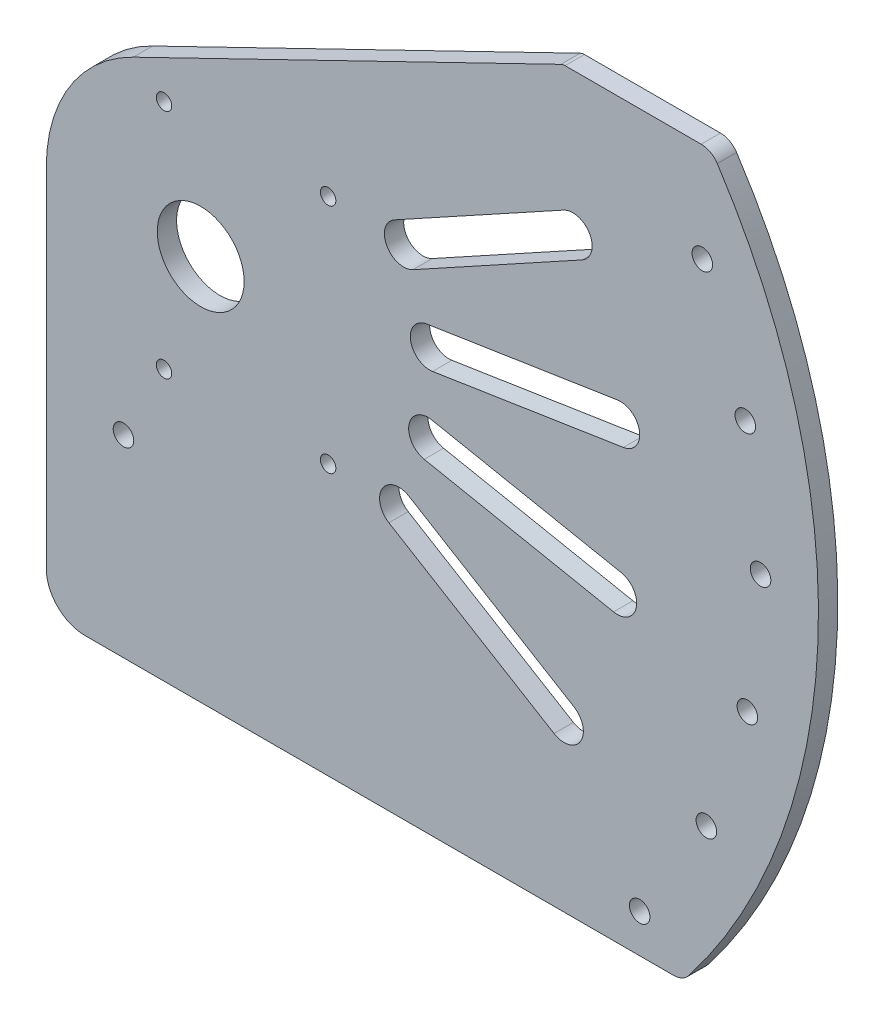
SolidWorks part; units mm, degrees
ref_plane "Front Plane" through (0, 0, 0) normal (0, 0, 1) x (1, 0, 0)
ref_plane "Top Plane" through (0, 0, 0) normal (0, 1, 0) x (1, 0, 0)
ref_plane "Right Plane" through (0, 0, 0) normal (1, 0, 0) x (0, 0, -1)
sketch "Sketch1" plane through (0, 0, 0) normal (0, 0, 1) x (1, 0, 0)
  line L1 (119.1366, 114.3) -> (164.6108, 114.3)
  line L2 (-50.8, 0) -> (-50.8, -114.3)
  line L3 (-38.1, -127) -> (155.5426, -127)
  line L8 (119.1366, 114.3) -> (-22.1838, 45.7003)
  line L12 (66.7662, 36.7249) -> (122.4047, 67.3289) construction
  line L13 (63.7058, 42.2887) -> (119.3443, 72.8927)
  line L14 (69.8266, 31.161) -> (125.4651, 61.765)
  line L16 (75.3003, 11.6747) -> (138.0506, 21.4036) construction
  line L17 (74.3275, 17.9497) -> (137.0777, 27.6786)
  line L18 (76.2732, 5.3997) -> (139.0235, 15.1286)
  line L20 (74.7522, -14.7836) -> (137.0456, -27.1033) construction
  line L21 (75.9841, -8.5543) -> (138.2776, -20.874)
  line L22 (73.5202, -21.013) -> (135.8136, -33.3326)
  line L24 (65.1878, -39.4588) -> (119.5109, -72.3411) construction
  line L25 (68.476, -34.0265) -> (122.7991, -66.9088)
  line L26 (61.8995, -44.8911) -> (116.2226, -77.7734)
  line L29 (36.6574, 35.1692) -> (119.1366, 114.3)
  line L35 (149.1104, -70.8808) -> (166.3251, -79.0426) construction
  line L37 (39.8301, -31.531) -> (144.384, -114.3) construction
  line L38 (32.4597, -39.0769) -> (105.4941, -127)
  circle A0 centre (0, 0) radius 14.2875
  circle A1 centre (0, 0) radius 50.8
  arc A2 (105.4941, -127) -> (119.1366, 114.3) centre (0, 0) ccw
  arc A3 (-50.8, -114.3) -> (-38.1, -127) centre (-38.1, -114.3) ccw
  arc A4 (160.5601, -124.5419) -> (169.9208, 111.4323) centre (0, 0) ccw
  arc A5 (133.35, -127) -> (142.263, -116.9294) centre (0, 0) ccw
  circle A6 centre (144.384, -114.3) radius 3.3782
  circle A7 centre (166.3251, -79.0426) radius 3.3782
  circle A8 centre (179.8084, -39.7654) radius 3.3782
  circle A9 centre (184.1483, 1.5342) radius 3.3782
  circle A10 centre (179.124, 42.7562) radius 3.3782
  circle A11 centre (164.9912, 81.8044) radius 3.3782
  arc A12 (167.7457, -75.9776) -> (179.0457, -43.0564) centre (0, 0) ccw
  arc A13 (146.4564, -111.6322) -> (164.8458, -82.0797) centre (0, 0) ccw
  arc A14 (180.5046, -36.4597) -> (184.1408, -1.844) centre (0, 0) ccw
  arc A15 (184.0845, 4.9118) -> (179.8721, 39.4619) centre (0, 0) ccw
  arc A16 (163.456, 84.8136) -> (144.384, 114.3) centre (0, 0) ccw
  arc A17 (178.3036, 46.0333) -> (166.4571, 78.7608) centre (0, 0) ccw
  arc A18 (169.9208, 111.4323) -> (164.6108, 114.3) centre (164.6108, 107.95) ccw
  arc A19 (160.5601, -124.5419) -> (155.5426, -127) centre (155.5426, -120.65) cw
  arc A20 (63.7058, 42.2887) -> (69.8266, 31.161) centre (66.7662, 36.7249) ccw
  arc A21 (125.4651, 61.765) -> (119.3443, 72.8927) centre (122.4047, 67.3289) ccw
  arc A22 (74.3275, 17.9497) -> (76.2732, 5.3997) centre (75.3003, 11.6747) ccw
  arc A23 (139.0235, 15.1286) -> (137.0777, 27.6786) centre (138.0506, 21.4036) ccw
  arc A24 (75.9841, -8.5543) -> (73.5202, -21.013) centre (74.7522, -14.7836) ccw
  arc A25 (135.8136, -33.3326) -> (138.2776, -20.874) centre (137.0456, -27.1033) ccw
  arc A26 (68.476, -34.0265) -> (61.8995, -44.8911) centre (65.1878, -39.4588) ccw
  arc A27 (116.2226, -77.7734) -> (122.7991, -66.9088) centre (119.5109, -72.3411) ccw
  circle A28 centre (-25.4, -63.5) radius 3.3782
  point P54 (94.5854, 52.0269)
  point P65 (106.6755, 16.5391)
  point P73 (105.8989, -20.9435)
  point P81 (92.3493, -55.9)
  dimension "D1" = 28.575
  dimension "D6" = 101.6
  dimension "D7" = 330.2
  dimension "D8" = 12.7
  dimension "D9" = 406.4
  dimension "D10" = 184.15
  dimension "D11" = 6.7564
  dimension "D15" = 6.35
  dimension "D19" = 6.35
  dimension "D14" = 63.5
  dimension "D5" = 6.7564
  dimension "D2" = 114.3
  dimension "D3" = 127
  dimension "D4" = 50.8
  dimension "D12" = 12.7
  dimension "D16" = 25.4
  dimension "D17" = 76.2
  dimension "D18" = 63.5
  dimension "D13" = 6
  dimension "D20" = 4
extrude "Boss-Extrude1" add sketch "Sketch1" along normal blind 6.35
fillet "Fillet1" radius 3.175 1 edges at (119.1366, 114.3, 3.175)
sketch "Sketch2" plane through (0, 0, 6.35) normal (0, 0, 1) x (1, 0, 0)
  line L0 (19.6773, 22.86) -> (19.6773, -22.86)
  line L1 (-24.7727, 50.8) -> (51.4273, 50.8)
  line L2 (-24.7727, 50.8) -> (-24.7727, -50.8)
  line L3 (-24.7727, -50.8) -> (51.4273, -50.8)
  line L4 (51.4273, 50.8) -> (51.4273, -50.8)
  line L5 (19.6773, 22.86) -> (0, 0)
  line L6 (0, 0) -> (19.6773, -22.86)
  circle A0 centre (19.6773, 22.86) radius 22.225
  circle A1 centre (19.6773, -22.86) radius 22.225
  circle A2 centre (-12.0727, 38.1) radius 2.54
  circle A3 centre (-12.0727, -38.1) radius 2.54
  circle A4 centre (41.9023, -38.1) radius 2.54
  circle A5 centre (41.9023, 38.1) radius 2.54
  point P4 (19.6773, 0)
  dimension "D7" = 50.8
  dimension "D8" = 44.45
  dimension "D4" = 44.45
  dimension "D12" = 5.08
  dimension "D13" = 5.08
  dimension "D16" = 5.08
  dimension "D17" = 5.08
  dimension "D1" = 0
  dimension "D2" = 45.72
  dimension "D3" = 30.1625
  dimension "D5" = 31.75
  dimension "D6" = 44.45
  dimension "D9" = 50.8
  dimension "D10" = 12.7
  dimension "D11" = 9.525
  dimension "D14" = 9.525
  dimension "D15" = 12.7
  dimension "D18" = 12.7
  dimension "D19" = 12.7
  dimension "D20" = 12.7
  dimension "D21" = 12.7
extrude "Cut-Extrude1" cut sketch "Sketch2" against normal up to surface (6.35 mm away) contours A2 | A5 | A4 | A3 up to face at (75.6332, 0.702, 0)
